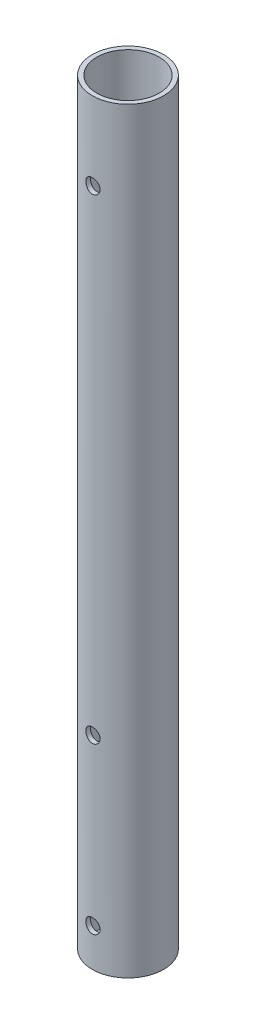
SolidWorks part; units mm, degrees
material "Thornel Mat VMA"
ref_plane "前视基准面" through (0, 0, 0) normal (0, 0, 1) x (1, 0, 0)
ref_plane "上视基准面" through (0, 0, 0) normal (0, 1, 0) x (1, 0, 0)
ref_plane "右视基准面" through (0, 0, 0) normal (1, 0, 0) x (0, 0, -1)
other "Configuration Table"
sketch "草图1" plane through (0, 0, 0) normal (0, 1, 0) x (1, 0, 0)
  circle A0 centre (0, 0) radius 8
  circle A1 centre (0, 0) radius 7
  dimension "D1" = 14
  dimension "D2" = 16
extrude "凸台-拉伸1" add sketch "草图1" along normal blind 169.65
sketch "草图3" plane through (0, 0, 0) normal (0, 0, 1) x (1, 0, 0)
  circle A0 centre (0, 152.15) radius 1.6
  circle A1 centre (0, 45.5) radius 1.6
  circle A2 centre (0, 8.5) radius 1.6
  dimension "D1" = 3.2
  dimension "D2" = 3.2
  dimension "D3" = 3.2
extrude "切除-拉伸1" cut sketch "草图3" against normal through all both and the other way through all
